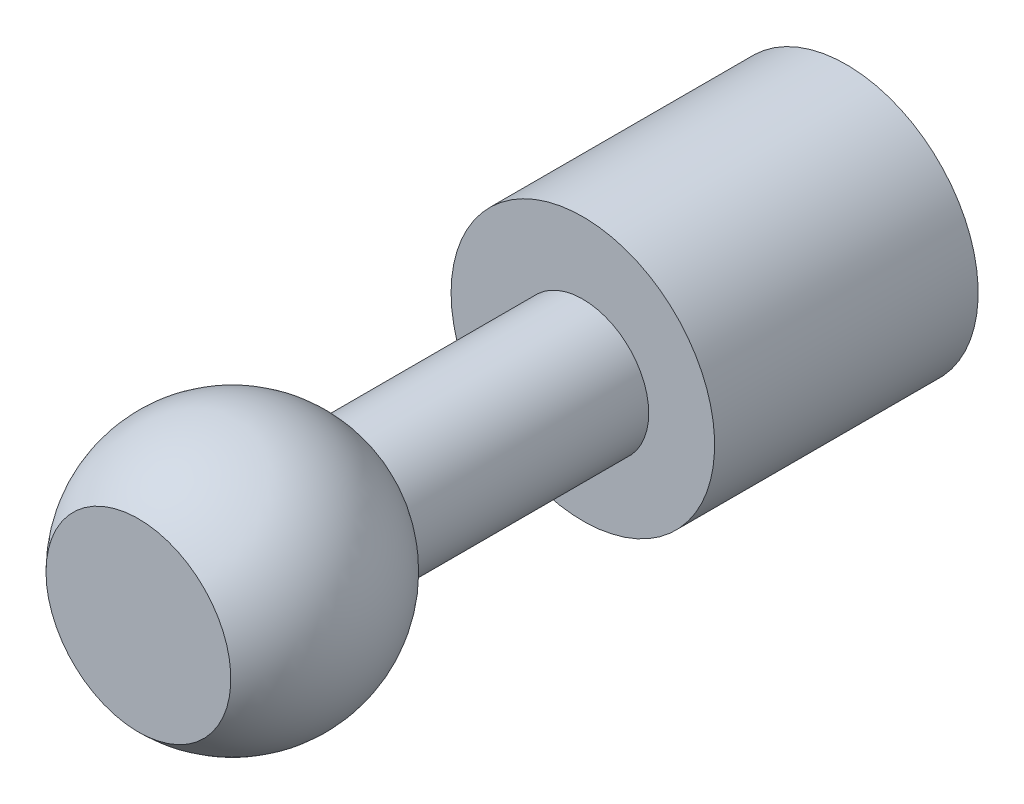
SolidWorks part; units mm, degrees
ref_plane "Front Plane" through (0, 0, 0) normal (0, 0, 1) x (1, 0, 0)
ref_plane "Top Plane" through (0, 0, 0) normal (0, 1, 0) x (1, 0, 0)
ref_plane "Right Plane" through (0, 0, 0) normal (1, 0, 0) x (0, 0, -1)
sketch "Sketch1" plane through (0, 0, 0) normal (0, 0, 1) x (1, 0, 0)
  circle A1 centre (0, -0.2104) radius 2.5
  point P4 (0, 0)
  dimension "D2" = 5
extrude "Boss-Extrude1" add sketch "Sketch1" along normal blind 9.1 contours A1
sketch "Sketch3" plane through (0, 0, 0) normal (1, 0, 0) x (0, 0, -1)
  line L0 (-13.3, -5) -> (-13.3, 5)
  line L2 (-9.1, 2.2896) -> (-9.1, -2.7104) construction
  arc A0 (-13.3, 5) -> (-13.3, -5) centre (-13.3, 0) cw
  dimension "1" = 10
  dimension "D2" = 4.2
revolve "Revolve1" add sketch "Sketch3" angle 360 about L0
sketch "Sketch4" plane through (0, 0, 0) normal (1, 0, 0) x (0, 0, -1)
  line L0 (-13.264, 4.9999) -> (-13.264, -4.9999)
  line L1 (-22.1615, -5.3018) -> (-16.864, -5.3018)
  line L2 (-22.1615, -5.3018) -> (-22.1615, 5.7337)
  line L3 (-22.1615, 5.7337) -> (-16.864, 5.7337)
  line L4 (-16.864, -5.3018) -> (-16.864, 5.7337)
  line L5 (-13.264, -4.9999) -> (-13.264, 4.9999)
  line L6 (-13.2694, -4.9999) -> (-13.2694, 4.9999)
  arc A0 (-8.855, 2.2895) -> (-9.0983, -2.7104) centre (-13.3, 0) ccw construction
  dimension "D1" = 3.6
  dimension "D2" = 0
extrude "Cut-Extrude1" cut sketch "Sketch4" against normal through all both and the other way through all contours L1 L4 L3 L2
sketch "Sketch5" plane through (0, 0, 0) normal (0, 0, -1) x (-1, 0, 0)
  circle A0 centre (0, 0) radius 5
  dimension "D1" = 10
extrude "Boss-Extrude2" add sketch "Sketch5" along normal blind 10
sketch "Sketch6" plane through (0, 0, -10) normal (0, 0, -1) x (-1, 0, 0)
  circle A0 centre (0, 0) radius 4
  dimension "D1" = 8
extrude "Cut-Extrude2" cut sketch "Sketch6" against normal blind 8 and the other way through all
